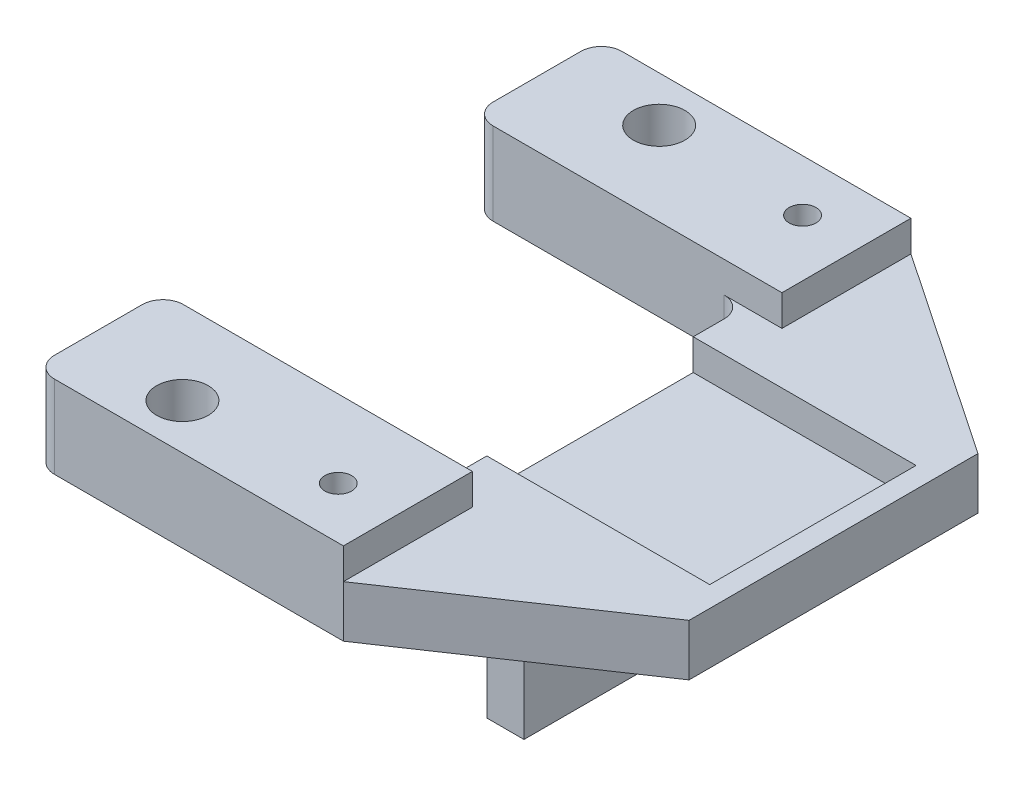
SolidWorks part; units mm, degrees
ref_plane "Front Plane" through (0, 0, 0) normal (0, 0, 1) x (1, 0, 0)
ref_plane "Top Plane" through (0, 0, 0) normal (0, 1, 0) x (1, 0, 0)
ref_plane "Right Plane" through (0, 0, 0) normal (1, 0, 0) x (0, 0, -1)
sketch "Sketch1" plane through (0, 0, 0) normal (0, 1, 0) x (1, 0, 0)
  line L0 (50.8, 11.557) -> (25.4, -5.588)
  line L1 (0, 0) -> (25.4, 0) construction
  line L2 (0, 0) -> (0, 58.674) construction
  line L3 (0, 58.674) -> (25.4, 58.674) construction
  line L4 (25.4, 0) -> (25.4, 58.674) construction
  line L5 (-12.7, 64.262) -> (25.4, 64.262)
  line L6 (-12.7, 64.262) -> (-12.7, -5.588)
  line L7 (-12.7, -5.588) -> (25.4, -5.588)
  line L8 (25.4, 64.262) -> (25.4, -5.588)
  line L9 (25.4, 47.117) -> (50.8, 47.117)
  line L10 (25.4, 47.117) -> (25.4, 11.557)
  line L11 (25.4, 11.557) -> (50.8, 11.557)
  line L12 (50.8, 47.117) -> (50.8, 11.557)
  line L13 (50.8, 47.117) -> (25.4, 64.262)
  circle A0 centre (0, 0) radius 3.175
  circle A1 centre (0, 58.674) radius 3.175
  point P16 (0, 57.2131)
  dimension "D1" = 6.35
  dimension "D3" = 6.35
  dimension "D2" = 58.674
  dimension "D4" = 25.4
  dimension "D5" = 69.85
  dimension "D6" = 5.588
  dimension "D7" = 38.1
  dimension "D8" = 25.4
  dimension "D9" = 35.56
  dimension "D10" = 17.145
extrude "Boss-Extrude1" add sketch "Sketch1" along normal blind 6.35 contours L8 L5 L6 L7 A1 A0 | L9 L13 L8 | L12 L9 L8 L11 | L11 L8 L0
sketch "Sketch2" plane through (0, 6.35, 0) normal (0, 1, 0) x (1, 0, 0)
  line L0 (50.8, 47.117) -> (50.8, 11.557) construction
  line L5 (25.4, 64.262) -> (25.4, -5.588) construction
  line L6 (50.8, 47.117) -> (-12.7, 47.117) construction
  line L7 (-12.7, 64.262) -> (-12.7, -5.588) construction
  line L8 (50.8, 11.557) -> (-12.7, 11.557) construction
  line L9 (20.828, 42.037) -> (48.26, 42.037)
  line L14 (20.828, 42.037) -> (20.828, 16.637)
  line L15 (20.828, 16.637) -> (48.26, 16.637)
  line L16 (48.26, 42.037) -> (48.26, 16.637)
  dimension "D1" = 27.432
  dimension "D2" = 25.4
  dimension "D3" = 5.08
  dimension "D4" = 2.54
extrude "Cut-Extrude1" cut sketch "Sketch2" against normal blind 3.81
sketch "Sketch3" plane through (0, 6.35, 0) normal (0, 1, 0) x (1, 0, 0)
  line L0 (-12.7, 64.262) -> (-12.7, -5.588) construction
  line L1 (-12.7, 48.387) -> (20.828, 48.387)
  line L2 (-12.7, 48.387) -> (-12.7, 10.287)
  line L3 (-12.7, 10.287) -> (20.828, 10.287)
  line L4 (20.828, 48.387) -> (20.828, 10.287)
  line L6 (20.828, 42.037) -> (20.828, 16.637) construction
  line L7 (-12.7, 64.262) -> (25.4, 64.262) construction
  dimension "D1" = 38.1
  dimension "D2" = 15.875
extrude "Cut-Extrude2" cut sketch "Sketch3" against normal through all
sketch "Sketch9" plane through (0, 0, 0) normal (0, -1, 0) x (1, 0, 0)
  line L0 (20.828, -10.287) -> (20.828, -48.387) construction
  line L1 (20.828, -16.637) -> (25.4, -16.637)
  line L2 (20.828, -16.637) -> (20.828, -42.037)
  line L3 (20.828, -42.037) -> (25.4, -42.037)
  line L4 (25.4, -16.637) -> (25.4, -42.037)
  line L5 (-12.7, -10.287) -> (20.828, -10.287) construction
  dimension "D1" = 25.4
  dimension "D2" = 25.4
  dimension "D3" = 6.35
extrude "Boss-Extrude5" add sketch "Sketch9" along normal blind 21.59
sketch "Sketch10" plane through (0, 6.35, 0) normal (0, 1, 0) x (1, 0, 0)
  line L0 (25.4, 64.262) -> (25.4, -5.588) construction
  line L1 (-12.7, 10.287) -> (20.828, 10.287) construction
  line L2 (-12.7, 48.387) -> (25.4, 48.387)
  line L3 (-12.7, 48.387) -> (-12.7, 64.262)
  line L4 (-12.7, 64.262) -> (25.4, 64.262)
  line L5 (25.4, 48.387) -> (25.4, 64.262)
  line L6 (-12.7, -5.588) -> (25.4, -5.588)
  line L7 (-12.7, -5.588) -> (-12.7, 10.287)
  line L8 (-12.7, 10.287) -> (25.4, 10.287)
  line L9 (25.4, -5.588) -> (25.4, 10.287)
  circle A0 centre (0, 58.674) radius 3.175
  circle A1 centre (0, 0) radius 3.175
  point P21 (0, 0)
  dimension "D1" = 6.35
extrude "Boss-Extrude6" add sketch "Sketch10" along normal blind 3.81 and the other way blind 0.0003
sketch "Sketch11" plane through (0, 10.16, 0) normal (0, 1, 0) x (1, 0, 0)
  line L0 (25.4, 64.262) -> (-12.7, 64.262) construction
  line L1 (-12.7, -5.588) -> (25.4, -5.588) construction
  circle A0 centre (18.415, 57.912) radius 1.651
  circle A1 centre (0, 58.674) radius 3.175 construction
  circle A2 centre (18.415, 0.762) radius 1.651
  circle A3 centre (0, 0) radius 3.175 construction
  point P8 (18.4309, -4.9021)
  dimension "D1" = 3.302
  dimension "D2" = 18.415
  dimension "D3" = 6.35
  dimension "D4" = 6.35
  dimension "D5" = 18.415
  dimension "D6" = 3.302
extrude "Cut-Extrude4" cut sketch "Sketch11" against normal blind 10.16 and the other way through all
fillet "Fillet4" radius 2.54 6 edges at (-12.7, 5.08, 5.588) (-12.7, 5.08, -64.262) (-12.7, 5.08, -48.387) (-12.7, 5.08, -10.287) (20.828, 3.175, -10.287) (20.828, 3.175, -48.387)
chamfer "Chamfer3" distance 1.905 angle 45 3 edges at (23.114, 0, -16.637) (23.114, 0, -42.037) (25.4, 0, -29.337)
